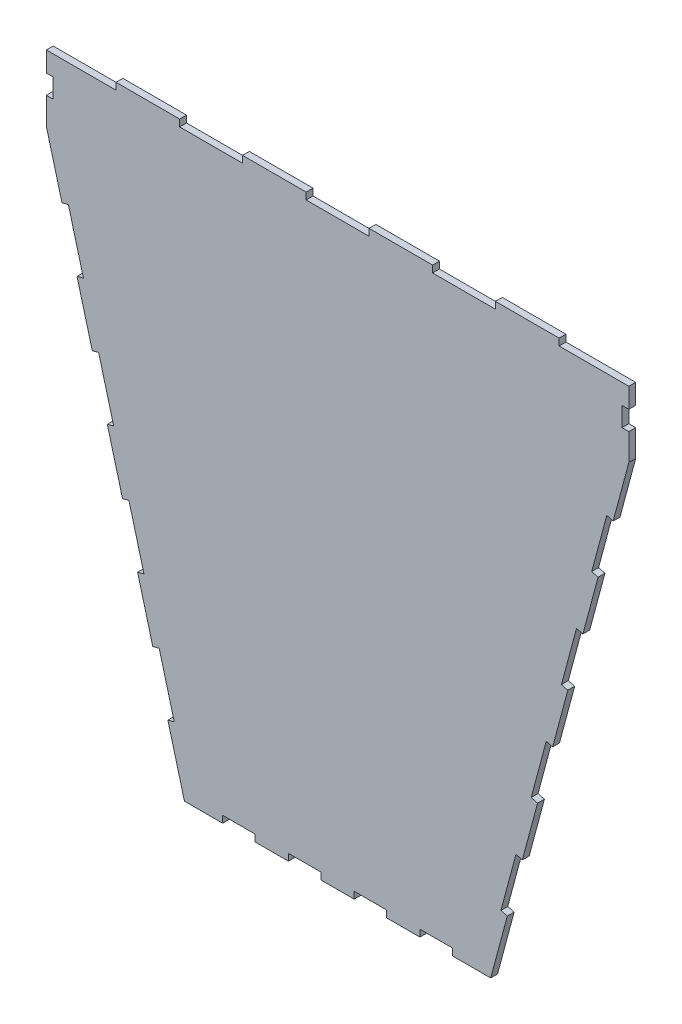
SolidWorks part; units mm, degrees
ref_plane "Front Plane" through (0, 0, 0) normal (0, 0, 1) x (1, 0, 0)
ref_plane "Top Plane" through (0, 0, 0) normal (0, 1, 0) x (1, 0, 0)
ref_plane "Right Plane" through (0, 0, 0) normal (1, 0, 0) x (0, 0, -1)
sketch "Sketch1" plane through (0, 0, 0) normal (0, 0, 1) x (1, 0, 0)
  line L0 (-124.8, 111.5883) -> (124.8, 111.5883)
  line L1 (124.8, 111.5883) -> (65, -111.5883)
  line L2 (65, -111.5883) -> (-65, -111.5883)
  line L3 (-65, -111.5883) -> (-124.8, 111.5883)
  point P4 (0, 111.5883)
  point P5 (94.9, 0)
  dimension "D1" = 130
  dimension "D2" = 249.6
  dimension "D3" = 75
extrude "Boss-Extrude1" add sketch "Sketch1" along normal blind 3
sketch "Sketch2" plane through (0, 0, 3) normal (0, 0, 1) x (1, 0, 0)
  line L2 (-124.8, 111.5883) -> (-124.8, 114.5883)
  line L9 (-124.8, 114.5883) -> (124.8, 114.5883)
  line L21 (124.8, 111.5883) -> (124.8, 114.5883)
  line L22 (-124.8, 111.5883) -> (124.8, 111.5883)
  line L28 (-124.8, 111.5883) -> (-65, -111.5883) construction
  line L29 (-65, -111.5883) -> (-50.4222, -111.5883)
  line L30 (-65, -111.5883) -> (-65, -114.5883)
  line L31 (-65, -114.5883) -> (-50.4222, -114.5883)
  line L32 (-50.4222, -111.5883) -> (-50.4222, -114.5883)
  line L33 (-65, -111.5883) -> (65, -111.5883) construction
  line L34 (-36.1444, -111.5883) -> (-50.4222, -111.5883) construction
  line L35 (-21.5667, -111.5883) -> (-36.1444, -111.5883)
  line L36 (-21.5667, -111.5883) -> (-21.5667, -114.5883)
  line L37 (-21.5667, -114.5883) -> (-36.1444, -114.5883)
  line L38 (-36.1444, -111.5883) -> (-36.1444, -114.5883)
  line L39 (-7.2889, -111.5883) -> (7.2889, -111.5883)
  line L40 (-7.2889, -111.5883) -> (-7.2889, -114.5883)
  line L41 (-7.2889, -114.5883) -> (7.2889, -114.5883)
  line L42 (7.2889, -111.5883) -> (7.2889, -114.5883)
  line L43 (21.5667, -111.5883) -> (36.1444, -111.5883)
  line L44 (21.5667, -111.5883) -> (21.5667, -114.5883)
  line L45 (21.5667, -114.5883) -> (36.1444, -114.5883)
  line L46 (36.1444, -111.5883) -> (36.1444, -114.5883)
  line L47 (65, -111.5883) -> (50.4222, -111.5883)
  line L48 (65, -111.5883) -> (65, -114.5883)
  line L49 (65, -114.5883) -> (50.4222, -114.5883)
  line L50 (50.4222, -111.5883) -> (50.4222, -114.5883)
  line L51 (-21.5667, -111.5883) -> (-7.2889, -111.5883) construction
  line L52 (7.2889, -111.5883) -> (21.5667, -111.5883) construction
  line L53 (36.1444, -111.5883) -> (50.4222, -111.5883) construction
  line L54 (-65, -113.0883) -> (-50.7222, -113.0883) construction
  line L55 (-50.7222, -113.0883) -> (-50.4222, -113.0883) construction
  dimension "D2" = 3
  dimension "D3" = 3
  dimension "D4" = 0.3
extrude "Boss-Extrude2" add sketch "Sketch2" against normal through all
sketch "Sketch4" plane through (0, 0, 3) normal (0, 0, 1) x (1, 0, 0)
  line L1 (-124.8, 140.5883) -> (-97.2, 140.5883)
  line L2 (-124.8, 131.8217) -> (-124.8, 123.355)
  line L3 (-124.8, 114.5883) -> (124.8, 114.5883)
  line L4 (124.8, 131.8217) -> (124.8, 123.355)
  line L5 (-97.2, 140.5883) -> (-97.2, 143.5883)
  line L6 (-97.2, 143.5883) -> (-69.3, 143.5883)
  line L7 (-69.3, 140.5883) -> (-69.3, 143.5883)
  line L8 (-41.7, 140.5883) -> (-41.7, 143.5883)
  line L9 (-41.7, 143.5883) -> (-13.8, 143.5883)
  line L10 (-13.8, 140.5883) -> (-13.8, 143.5883)
  line L11 (13.8, 140.5883) -> (13.8, 143.5883)
  line L12 (13.8, 143.5883) -> (41.7, 143.5883)
  line L13 (41.7, 140.5883) -> (41.7, 143.5883)
  line L14 (69.3, 140.5883) -> (69.3, 143.5883)
  line L15 (69.3, 143.5883) -> (97.2, 143.5883)
  line L16 (97.2, 140.5883) -> (97.2, 143.5883)
  line L29 (-124.8, 140.5883) -> (-127.8, 140.5883)
  line L30 (-124.8, 131.8217) -> (-127.8, 131.8217)
  line L31 (-127.8, 140.5883) -> (-127.8, 131.8217)
  line L32 (-124.8, 114.5883) -> (-127.8, 114.5883)
  line L33 (-124.8, 123.355) -> (-127.8, 123.355)
  line L34 (-127.8, 114.5883) -> (-127.8, 123.355)
  line L35 (124.8, 114.5883) -> (127.8, 114.5883)
  line L36 (124.8, 123.355) -> (127.8, 123.355)
  line L37 (127.8, 114.5883) -> (127.8, 123.355)
  line L38 (124.8, 140.5883) -> (127.8, 140.5883)
  line L39 (124.8, 131.8217) -> (127.8, 131.8217)
  line L40 (127.8, 140.5883) -> (127.8, 131.8217)
  line L44 (97.2, 140.5883) -> (124.8, 140.5883)
  line L45 (41.7, 140.5883) -> (69.3, 140.5883)
  line L46 (-13.8, 140.5883) -> (13.8, 140.5883)
  line L47 (-69.3, 140.5883) -> (-41.7, 140.5883)
  line L48 (-97.2, 140.5883) -> (-69.6, 140.5883) construction
  line L49 (-69.6, 140.5883) -> (-69.3, 140.5883) construction
  line L50 (-124.8, 131.8217) -> (-124.8, 140.2883) construction
  line L51 (-124.8, 140.2883) -> (-124.8, 140.5883) construction
  line L53 (-124.8, 114.5883) -> (124.8, 114.5883) construction
  point P20 (0, 0)
  point P21 (-97.2, 117.2182)
  point P22 (0, 114.5883)
  point P23 (123.3376, 121.2641)
  point P48 (0, 140.5883)
  point P49 (-124.8, 127.5883)
  dimension "D1" = 3
  dimension "D2" = 0.3
  dimension "D3" = 249.6
  dimension "D4" = 26
extrude "Boss-Extrude5" add sketch "Sketch4" against normal through all
sketch "Sketch3" plane through (0, 0, 3) normal (0, 0, 1) x (1, 0, 0)
  line L0 (124.8, 114.5883) -> (124.8, 111.5883)
  line L1 (124.8, 111.5883) -> (118.121, 86.6621)
  line L2 (124.8, 111.5883) -> (127.599, 110.8383) construction
  line L3 (118.121, 86.6621) -> (120.9201, 85.9121)
  line L4 (127.599, 110.8383) -> (120.9201, 85.9121)
  line L5 (65, -111.5883) -> (124.8, 111.5883) construction
  line L6 (111.5197, 62.0257) -> (104.8408, 37.0995)
  line L7 (111.5197, 62.0257) -> (114.3188, 61.2757)
  line L8 (104.8408, 37.0995) -> (107.6398, 36.3495)
  line L9 (114.3188, 61.2757) -> (107.6398, 36.3495)
  line L10 (98.2395, 12.4631) -> (91.5605, -12.4631)
  line L11 (98.2395, 12.4631) -> (101.0385, 11.7131)
  line L12 (91.5605, -12.4631) -> (94.3596, -13.2131)
  line L13 (101.0385, 11.7131) -> (94.3596, -13.2131)
  line L14 (84.9592, -37.0995) -> (78.2803, -62.0257)
  line L15 (84.9592, -37.0995) -> (87.7583, -37.8495)
  line L16 (78.2803, -62.0257) -> (81.0793, -62.7757)
  line L17 (87.7583, -37.8495) -> (81.0793, -62.7757)
  line L18 (65, -111.5883) -> (71.679, -86.6621)
  line L20 (71.679, -86.6621) -> (74.478, -87.4121)
  line L21 (67.799, -112.3383) -> (74.478, -87.4121)
  line L22 (65, -111.5883) -> (65, -114.5883)
  line L23 (67.799, -112.3383) -> (65, -111.5883) construction
  line L24 (-127.599, 110.8383) -> (-127.8, 111.5883)
  line L26 (118.121, 86.6621) -> (111.5197, 62.0257)
  line L27 (104.8408, 37.0995) -> (98.2395, 12.4631)
  line L28 (91.5605, -12.4631) -> (84.9592, -37.0995)
  line L29 (71.679, -86.6621) -> (78.2803, -62.0257)
  line L30 (119.5206, 86.2871) -> (126.1219, 110.9235) construction
  line L31 (126.1219, 110.9235) -> (126.1995, 111.2133) construction
  line L32 (0, 114.5883) -> (0, -114.5883) construction
  line L33 (-124.8, 111.5883) -> (-124.8, 114.5883) construction
  line L36 (-126.1219, 110.9235) -> (-126.1995, 111.2133) construction
  line L37 (-119.5206, 86.2871) -> (-126.1219, 110.9235) construction
  line L38 (-71.679, -86.6621) -> (-78.2803, -62.0257)
  line L39 (-91.5605, -12.4631) -> (-84.9592, -37.0995)
  line L40 (-104.8408, 37.0995) -> (-98.2395, 12.4631)
  line L41 (-118.121, 86.6621) -> (-111.5197, 62.0257)
  line L42 (-67.799, -112.3383) -> (-67.1962, -114.5883)
  line L43 (65, -114.5883) -> (67.1962, -114.5883)
  line L44 (-65, -111.5883) -> (-65, -114.5883)
  line L45 (-67.799, -112.3383) -> (-74.478, -87.4121)
  line L46 (-71.679, -86.6621) -> (-74.478, -87.4121)
  line L47 (67.1962, -114.5883) -> (67.799, -112.3383)
  line L48 (-65, -111.5883) -> (-71.679, -86.6621)
  line L49 (-87.7583, -37.8495) -> (-81.0793, -62.7757)
  line L50 (-78.2803, -62.0257) -> (-81.0793, -62.7757)
  line L51 (-84.9592, -37.0995) -> (-87.7583, -37.8495)
  line L52 (-84.9592, -37.0995) -> (-78.2803, -62.0257)
  line L53 (-101.0385, 11.7131) -> (-94.3596, -13.2131)
  line L54 (-91.5605, -12.4631) -> (-94.3596, -13.2131)
  line L55 (-98.2395, 12.4631) -> (-101.0385, 11.7131)
  line L56 (-98.2395, 12.4631) -> (-91.5605, -12.4631)
  line L57 (-114.3188, 61.2757) -> (-107.6398, 36.3495)
  line L58 (-104.8408, 37.0995) -> (-107.6398, 36.3495)
  line L59 (-111.5197, 62.0257) -> (-114.3188, 61.2757)
  line L60 (-111.5197, 62.0257) -> (-104.8408, 37.0995)
  line L61 (-127.599, 110.8383) -> (-120.9201, 85.9121)
  line L62 (-118.121, 86.6621) -> (-120.9201, 85.9121)
  line L63 (-124.8, 111.5883) -> (-127.599, 110.8383) construction
  line L64 (-124.8, 111.5883) -> (-118.121, 86.6621)
  line L65 (-124.8, 114.5883) -> (-124.8, 111.5883)
  line L66 (127.599, 110.8383) -> (127.8, 111.5883)
  line L67 (127.8, 111.5883) -> (127.8, 114.5883)
  line L68 (127.8, 114.5883) -> (124.8, 114.5883)
  line L69 (-127.8, 111.5883) -> (-127.8, 114.5883)
  line L70 (-127.8, 114.5883) -> (-124.8, 114.5883)
  line L71 (-67.1962, -114.5883) -> (-65, -114.5883)
  line L72 (65, -114.5883) -> (50.4222, -114.5883) construction
  point P9 (-127.8, 114.5883)
  point P29 (-124.8, 114.5883)
  point P34 (0, 114.5883)
  dimension "D1" = 0.3
  dimension "D2" = 2.8978
  dimension "D3" = 2.3294
extrude "Boss-Extrude4" add sketch "Sketch3" against normal through all
